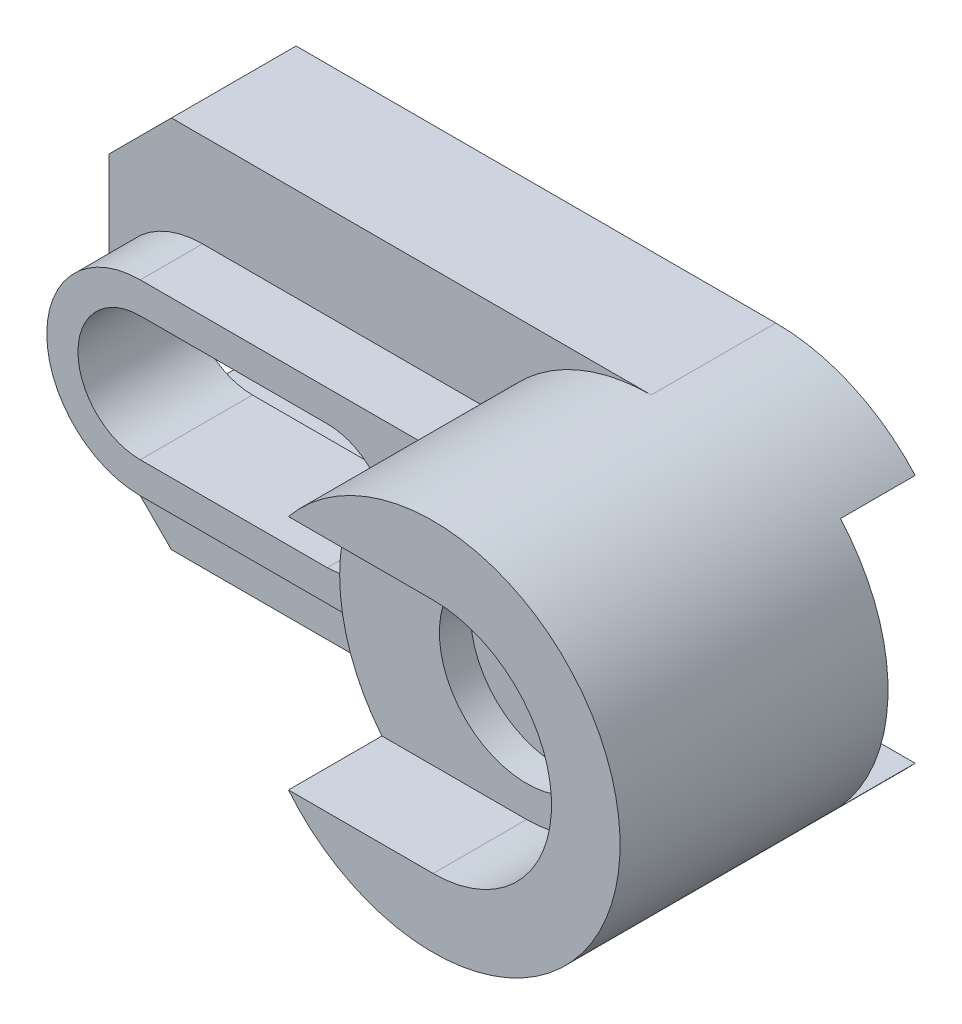
SolidWorks part; units mm, degrees
ref_plane "Plano frontal" through (0, 0, 0) normal (0, 0, 1) x (1, 0, 0)
ref_plane "Plano superior" through (0, 0, 0) normal (0, 1, 0) x (1, 0, 0)
ref_plane "Plano direito" through (0, 0, 0) normal (1, 0, 0) x (0, 0, -1)
sketch "Esboço3" plane through (0, 0, 0) normal (0, 0, 1) x (1, 0, 0)
  circle A0 centre (0, 0) radius 30
extrude "Ressalto-extrusão1" add sketch "Esboço3" against normal blind 55
sketch "Esboço4" plane through (0, 0, -55) normal (0, 0, -1) x (-1, 0, 0)
  line L0 (0, 30) -> (87, 30)
  line L1 (87, 30) -> (87, -30)
  line L2 (87, -30) -> (0, -30)
  circle A0 centre (0, 0) radius 30 construction
  circle A2 centre (0, 0) radius 30
  arc A3 (0, -30) -> (0, 30) centre (0, 0) ccw
  dimension "D1" = 87
  dimension "D2" = 87
  dimension "D3" = 60
  dimension "D4" = 0
extrude "Ressalto-extrusão2" add sketch "Esboço4" against normal blind 20
sketch "Esboço6" plane through (0, 0, 0) normal (0, 0, 1) x (1, 0, 0)
  line L1 (0, -19) -> (-43.2512, -19)
  line L3 (0, 19) -> (-43.2512, 19)
  line L4 (-43.2512, -19) -> (-43.2512, 19)
  arc A0 (0, -19) -> (0, 19) centre (0, 0) ccw
extrude "Corte-extrusão2" cut sketch "Esboço6" against normal blind 15
sketch "Esboço9" plane through (0, 0, -15) normal (0, 0, 1) x (1, 0, 0)
  circle A0 centre (0, 0) radius 14
  circle A1 centre (0, 0) radius 1
  point P0 (-129.4799, 4.3174)
  dimension "D1" = 28
extrude "Corte-extrusão6" cut sketch "Esboço9" against normal blind 5
sketch "Esboço12" plane through (0, 0, -20) normal (0, 0, 1) x (1, 0, 0)
  circle A0 centre (0.1674, 0.0425) radius 6
extrude "Corte-extrusão7" cut sketch "Esboço12" against normal blind 65
chamfer "Chanfro2" distance 10 angle 45 1 edges at (-87, 30, -45)
chamfer "Chanfro3" distance 10 angle 45 1 edges at (-87, -30, -45)
sketch "Esboço14" plane through (0, 0, -35) normal (0, 0, 1) x (1, 0, 0)
  line L0 (-87, -20) -> (-87, 20) construction
  line L1 (-72, 15) -> (-25.9808, 15)
  line L2 (-72, -15) -> (-25.9808, -15)
  arc A1 (-72, 15) -> (-72, -15) centre (-72, 0) ccw
  arc A2 (-25.9808, 15) -> (-25.9808, -15) centre (0, 0) ccw
  point P7 (-87, 0)
  dimension "D1" = 15
extrude "Ressalto-extrusão4" add sketch "Esboço14" along normal blind 10
sketch "Esboço15" plane through (0, 0, -25) normal (0, 0, 1) x (1, 0, 0)
  line L0 (-87, 0) -> (-87, 20) construction
  line L1 (-72, 10) -> (-42, 10)
  line L2 (-72, -10) -> (-42, -10)
  arc A0 (-72, 10) -> (-72, -10) centre (-72, 0) ccw
  arc A1 (-42, -10) -> (-42, 10) centre (-42, 0) ccw
  dimension "D1" = 15
  dimension "D2" = 30
extrude "Corte-extrusão8" cut sketch "Esboço15" against normal blind 54
sketch "Esboço16" plane through (-87, 0, 0) normal (-1, 0, 0) x (0, 0, 1)
  line L0 (-35, 20) -> (-55, 20) construction
  line L1 (-43, 20) -> (-55, 20)
  line L2 (-43, 20) -> (-43, -20)
  line L3 (-43, -20) -> (-55, -20)
  line L4 (-55, 20) -> (-55, -20)
  line L5 (-55, -20) -> (-35, -20) construction
  line L7 (-55, 20) -> (-55, 30) construction
  dimension "D1" = 12
extrude "Corte-extrusão9" cut sketch "Esboço16" against normal blind 124
